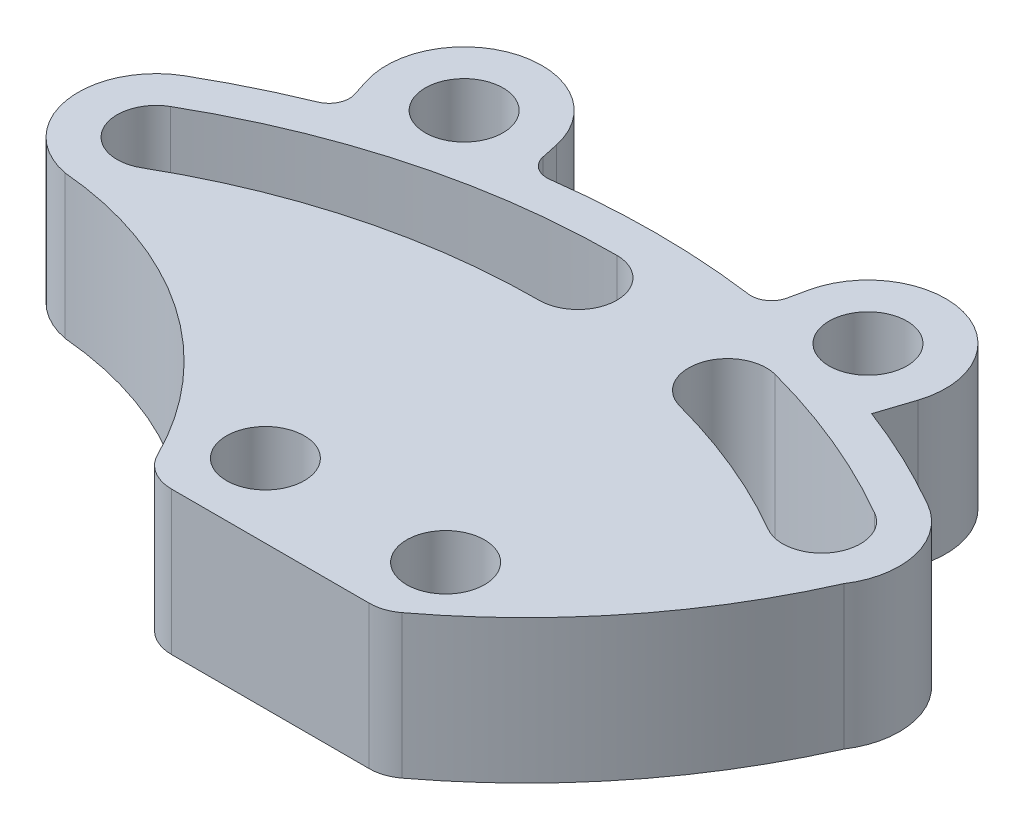
SolidWorks part; units mm, degrees
ref_plane "Front Plane" through (0, 0, 0) normal (0, 0, 1) x (1, 0, 0)
ref_plane "Top Plane" through (0, 0, 0) normal (0, 1, 0) x (1, 0, 0)
ref_plane "Right Plane" through (0, 0, 0) normal (1, 0, 0) x (0, 0, -1)
sketch "Sketch2" plane through (0, 0, 0) normal (0, 1, 0) x (1, 0, 0)
  line L0 (0, 44.45) -> (0, -44.45) construction
  line L1 (0, -44.45) -> (-28.2118, 60.8379) construction
  line L2 (0, -44.45) -> (-54.8566, 50.5644) construction
  line L3 (0, -44.45) -> (54.8566, 50.5644) construction
  line L4 (0, -44.45) -> (28.2118, 60.8379) construction
  line L5 (-34.2339, 46.0666) -> (-33.5597, 43.9741)
  line L6 (-15.6109, 51.0566) -> (-15.1485, 48.9074)
  line L7 (34.2339, 46.0666) -> (32.813, 41.7156)
  line L8 (15.6109, 51.0566) -> (15.1485, 48.9074)
  line L9 (-2.5146, -9.7989) -> (22.0058, -9.7989)
  circle A0 centre (0, -0.6682) radius 4.826
  circle A1 centre (22.352, -0.6682) radius 4.826
  arc A2 (-41.275, 27.0404) -> (0, 38.1) centre (0, -44.45) cw construction
  arc A3 (0, 42.926) -> (-43.688, 31.2198) centre (0, -44.45) ccw
  arc A4 (0, 33.274) -> (-38.862, 22.861) centre (0, -44.45) ccw
  arc A5 (0, 33.274) -> (0, 42.926) centre (0, 38.1) ccw
  arc A6 (-43.688, 31.2198) -> (-38.862, 22.861) centre (-41.275, 27.0404) ccw
  arc A7 (41.275, 27.0404) -> (21.3655, 35.2872) centre (0, -44.45) ccw construction
  arc A8 (43.688, 31.2198) -> (22.6146, 39.9487) centre (0, -44.45) ccw
  arc A9 (38.862, 22.861) -> (20.1165, 30.6256) centre (0, -44.45) ccw
  arc A10 (38.862, 22.861) -> (43.688, 31.2198) centre (41.275, 27.0404) ccw
  arc A11 (22.6146, 39.9487) -> (20.1165, 30.6256) centre (21.3655, 35.2872) ccw
  arc A14 (-48.387, 39.3587) -> (48.387, 39.3587) centre (0, -44.45) cw construction
  circle A15 centre (-25.047, 49.0265) radius 4.826
  arc A18 (-41.275, 27.0404) -> (41.275, 27.0404) centre (0, -44.45) cw construction
  arc A21 (-46.101, 35.3993) -> (-35.0128, 40.8454) centre (0, -44.45) cw
  circle A23 centre (25.047, 49.0265) radius 4.826
  arc A24 (-35.0128, 40.8454) -> (-33.5597, 43.9741) centre (-35.9773, 43.1952) ccw
  arc A25 (50.4607, 20.8816) -> (-48.7573, 22.1625) centre (0, -44.45) ccw construction
  arc A26 (12.3257, 46.9244) -> (-12.3257, 46.9244) centre (0, -44.45) ccw
  arc A27 (-15.1485, 48.9074) -> (-12.3257, 46.9244) centre (-12.6653, 49.4416) ccw
  arc A28 (15.1485, 48.9074) -> (12.3257, 46.9244) centre (12.6653, 49.4416) cw
  arc A29 (32.813, 41.7156) -> (46.101, 35.3993) centre (0, -44.45) cw
  arc A30 (46.101, 35.3993) -> (49.3374, 21.734) centre (41.275, 27.0404) cw
  arc A31 (49.3374, 21.734) -> (25.0606, -8.7778) centre (-21.6775, 53.3235) cw
  arc A32 (-46.101, 35.3993) -> (-43.077, 17.5581) centre (-41.275, 27.0404) ccw
  arc A33 (-43.077, 17.5581) -> (-7.0655, -6.9763) centre (-46.8858, -26.7284) cw
  arc A34 (-2.5146, -9.7989) -> (-7.0655, -6.9763) centre (-2.5146, -4.7189) cw
  arc A35 (22.0058, -9.7989) -> (25.0606, -8.7778) centre (22.0058, -4.7189) ccw
  arc A36 (-34.2339, 46.0666) -> (-15.6109, 51.0566) centre (-25.047, 49.0265) cw
  arc A37 (15.6109, 51.0566) -> (34.2339, 46.0666) centre (25.047, 49.0265) cw
  point P5 (0, 0)
  point P10 (-21.3655, 35.2872)
  point P20 (31.5905, 31.8163)
  point P57 (-14.648, 46.581)
  dimension "D3" = 22.352
  dimension "D4" = 2.54
  dimension "D5" = 2.54
  dimension "D6" = 2.54
  dimension "D7" = 5.08
  dimension "D8" = 5.08
  dimension "D1" = 15
  dimension "D2" = 15
extrude "Boss-Extrude1" add sketch "Sketch2" along normal blind 17.78 contours A37 L8 A28 A26 A27 L6 A36 L5 A24 A21 A32 A33 A34 L9 A35 A31 A30 A29 L7 A0 A1 A6 A3 A5 A4 A11 A8 A10 A9 A15 A23
